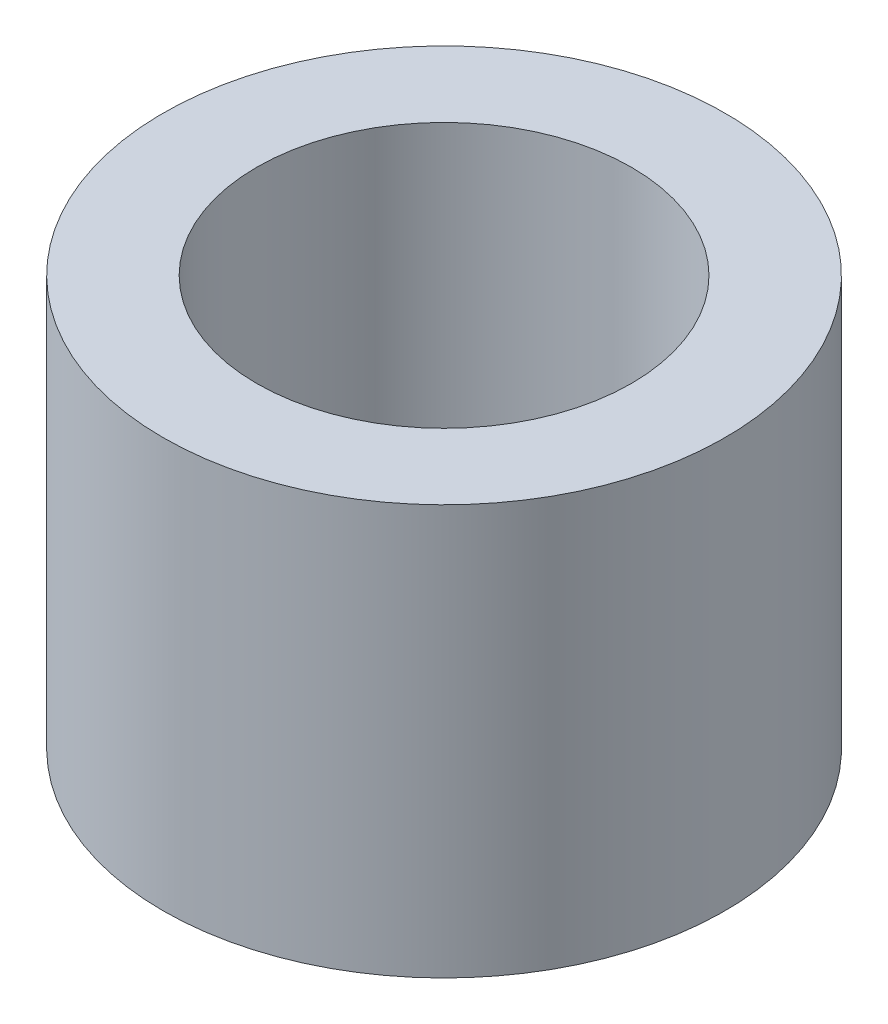
SolidWorks part; units mm, degrees
ref_plane "Front Plane" through (0, 0, 0) normal (0, 0, 1) x (1, 0, 0)
ref_plane "Top Plane" through (0, 0, 0) normal (0, 1, 0) x (1, 0, 0)
ref_plane "Right Plane" through (0, 0, 0) normal (1, 0, 0) x (0, 0, -1)
sketch "Sketch1" plane through (0, 0, 0) normal (0, 1, 0) x (1, 0, 0)
  circle A0 centre (0, 0) radius 1.6
  circle A1 centre (0, 0) radius 2.4
  dimension "D1" = 3.2
  dimension "D2" = 4.8
extrude "Boss-Extrude1" add sketch "Sketch1" along normal blind 3.5
